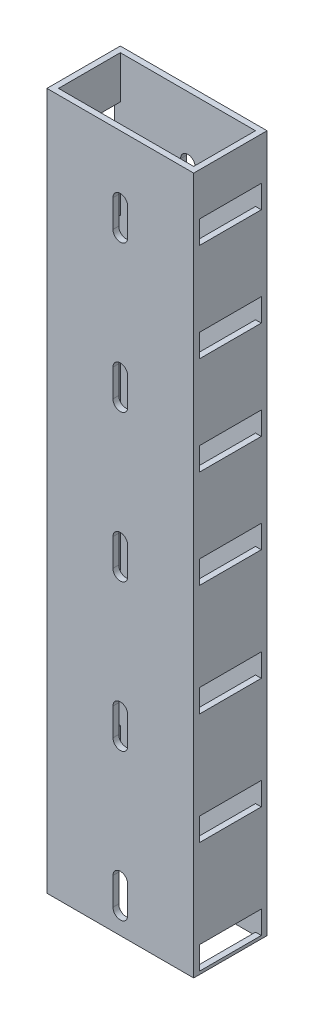
SolidWorks part; units mm, degrees
ref_plane "Front Plane" through (0, 0, 0) normal (0, 0, 1) x (1, 0, 0)
ref_plane "Top Plane" through (0, 0, 0) normal (0, 1, 0) x (1, 0, 0)
ref_plane "Right Plane" through (0, 0, 0) normal (1, 0, 0) x (0, 0, -1)
sketch "Sketch1" plane through (0, 0, 0) normal (0, 1, 0) x (1, 0, 0)
  line L0 (0, 25.4) -> (50.8, 0) construction
  line L1 (0, 0) -> (50.8, 0)
  line L2 (0, 0) -> (0, 25.4)
  line L3 (0, 25.4) -> (50.8, 25.4)
  line L4 (50.8, 0) -> (50.8, 25.4)
  line L6 (2, 23.4) -> (48.8, 23.4)
  line L7 (2, 23.4) -> (2, 2)
  line L8 (2, 2) -> (48.8, 2)
  line L9 (48.8, 23.4) -> (48.8, 2)
  line L10 (2, 23.4) -> (48.8, 2) construction
  line L11 (2, 2) -> (48.8, 23.4) construction
  point P5 (25.4, 12.7)
  dimension "D1" = 50.8
  dimension "D2" = 25.4
  dimension "D3" = 2
  dimension "D4" = 2
extrude "Boss-Extrude1" add sketch "Sketch1" against normal offset from surface (241.3 mm away) 50.8
sketch "Sketch2" plane through (50.8, 0, 0) normal (1, 0, 0) x (0, 0, -1)
  line L0 (2, -241.3) -> (2, 0) construction
  line L1 (2, -241.3) -> (2, 0)
  line L2 (23.4, -241.3) -> (23.4, 0) construction
  line L3 (23.4, -241.3) -> (23.4, 0)
  line L4 (23.4, -120.65) -> (2, -120.65) construction
  line L6 (2, -116.6813) -> (23.4, -116.6813)
  line L7 (2, -116.6813) -> (2, -124.6188)
  line L8 (2, -124.6188) -> (23.4, -124.6188)
  line L9 (23.4, -116.6813) -> (23.4, -124.6188)
  line L10 (2, -116.6813) -> (23.4, -124.6188) construction
  line L11 (2, -124.6188) -> (23.4, -116.6813) construction
  point P6 (12.7, -120.65)
  dimension "D1" = 7.9375
extrude "Cut-Extrude1" cut sketch "Sketch2" against normal through all contours L1 L8 L3 L6
pattern_linear "LPattern1" count 4 spacing 33.9725 along (0, 1, 0) count 4 spacing 38.5445 along (0, -1, 0) of "Cut-Extrude1"
sketch "Sketch3" plane through (0, 0, -25.4) normal (0, 0, -1) x (-1, 0, 0)
  line L0 (-25.4, 0) -> (-25.4, -241.3) construction
  line L1 (-25.4, -21.336) -> (-25.4, -30.861) construction
  line L2 (-22.86, -21.336) -> (-22.86, -30.861)
  line L3 (-27.94, -21.336) -> (-27.94, -30.861)
  line L4 (-50.8, -241.3) -> (0, -241.3)
  line L5 (0, -241.3) -> (0, 0)
  line L6 (0, 0) -> (-50.8, 0)
  line L7 (-50.8, 0) -> (-50.8, -241.3)
  line L8 (-50.8, -241.3) -> (0, -241.3) construction
  line L9 (0, -241.3) -> (0, 0) construction
  line L10 (0, 0) -> (-50.8, 0) construction
  line L11 (-50.8, 0) -> (-50.8, -241.3) construction
  arc A0 (-22.86, -21.336) -> (-27.94, -21.336) centre (-25.4, -21.336) ccw
  arc A1 (-27.94, -30.861) -> (-22.86, -30.861) centre (-25.4, -30.861) ccw
  point P8 (-25.4, -26.0985)
  point P13 (-25.4, -18.796)
  point P14 (-25.4, -33.401)
  dimension "D3" = 2.54
  dimension "D2" = 18.796
  dimension "D4" = 14.605
  dimension "D1" = 0
extrude "Cut-Extrude2" cut sketch "Sketch3" against normal through all
pattern_linear "LPattern2" count 5 spacing 50.8 along (0, -1, 0) of "Cut-Extrude2"
ref_plane "Plane1" through (25.4, 0, 0) normal (-1, 0, 0) x (0, 0, 1)
